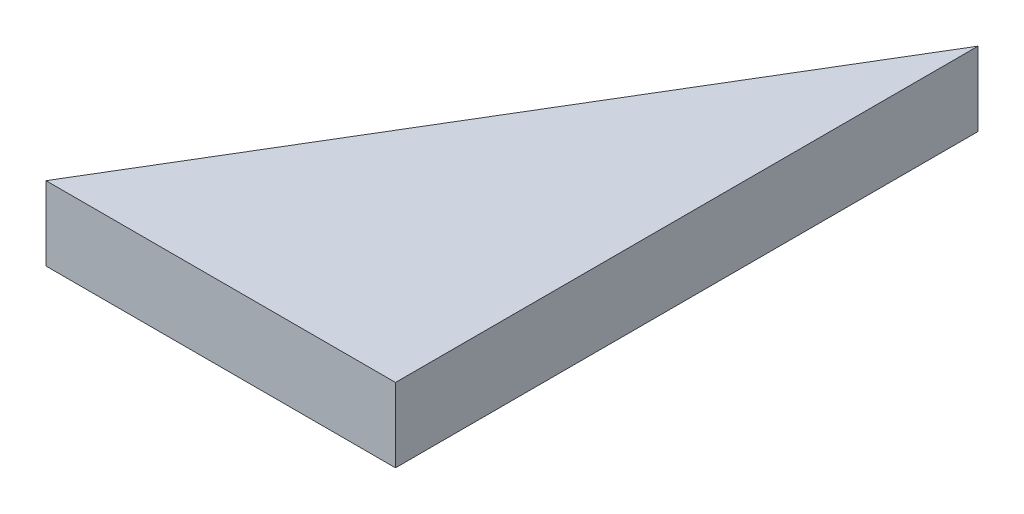
SolidWorks part; units mm, degrees
ref_plane "Plan de face" through (0, 0, 0) normal (0, 0, 1) x (1, 0, 0)
ref_plane "Plan de dessus" through (0, 0, 0) normal (0, 1, 0) x (1, 0, 0)
ref_plane "Plan de droite" through (0, 0, 0) normal (1, 0, 0) x (0, 0, -1)
sketch "Esquisse1" plane through (0, 0, 0) normal (0, 1, 0) x (1, 0, 0)
  line L0 (-30, 0) -> (0, 0)
  line L1 (0, 0) -> (0, 50)
  line L2 (0, 50) -> (-30, 0)
  line L3 (-55, 0) -> (55, 0) construction
  point P4 (-24.0102, -10.9792)
  point P7 (-15, 0)
  dimension "D1" = 50
  dimension "D2" = 30
extrude "Boss.-Extru.1" add sketch "Esquisse1" along normal blind 6.35
